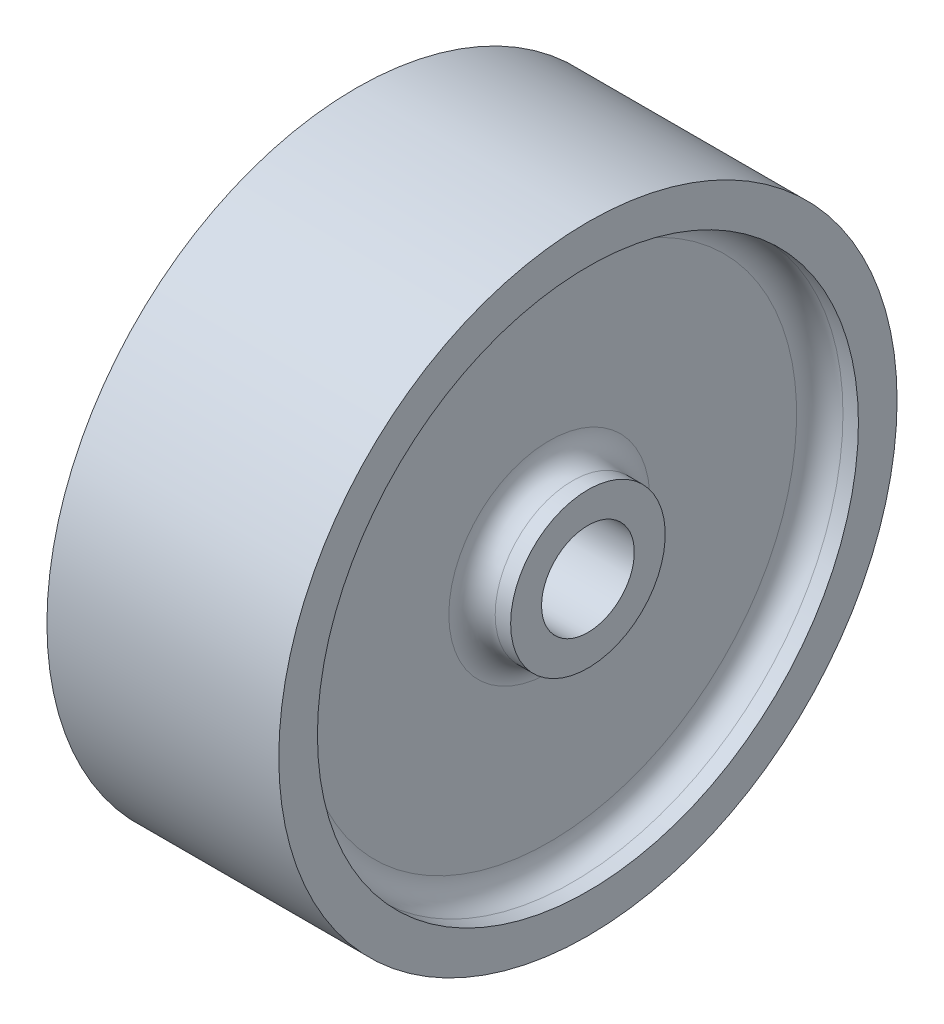
SolidWorks part; units mm, degrees
material "PP Homopolymer"
ref_plane "Front Plane" through (0, 0, 0) normal (0, 0, 1) x (1, 0, 0)
ref_plane "Top Plane" through (0, 0, 0) normal (0, 1, 0) x (1, 0, 0)
ref_plane "Right Plane" through (0, 0, 0) normal (1, 0, 0) x (0, 0, -1)
sketch "Sketch2" plane through (0, 0, 0) normal (0, 0, 1) x (1, 0, 0)
  line L0 (-15, 0) -> (15, 0) construction
  line L13 (0, 0) -> (0, 40) construction
  line L14 (-15, 40) -> (15, 40)
  line L15 (15, 40) -> (15, 35)
  line L16 (15, 35) -> (13, 35)
  line L17 (10, 32) -> (10, 13)
  line L18 (13, 10) -> (15, 10)
  line L19 (15, 10) -> (15, 6)
  line L20 (15, 6) -> (-15, 6)
  line L21 (-15, 10) -> (-15, 6)
  line L22 (-13, 10) -> (-15, 10)
  line L23 (-10, 32) -> (-10, 13)
  line L24 (-15, 35) -> (-13, 35)
  line L25 (-15, 40) -> (-15, 35)
  arc A0 (10, 13) -> (13, 10) centre (13, 13) ccw
  arc A1 (10, 32) -> (13, 35) centre (13, 32) cw
  arc A2 (-10, 32) -> (-13, 35) centre (-13, 32) ccw
  arc A3 (-10, 13) -> (-13, 10) centre (-13, 13) cw
  point P4 (0, 0)
  point P19 (0, 6)
  dimension "D7" = 3
  dimension "D1" = 30
  dimension "D2" = 40
  dimension "D3" = 6
  dimension "D4" = 10
  dimension "D5" = 35
  dimension "D6" = 10
revolve "Revolve1" add sketch "Sketch2" angle 360 about L0
